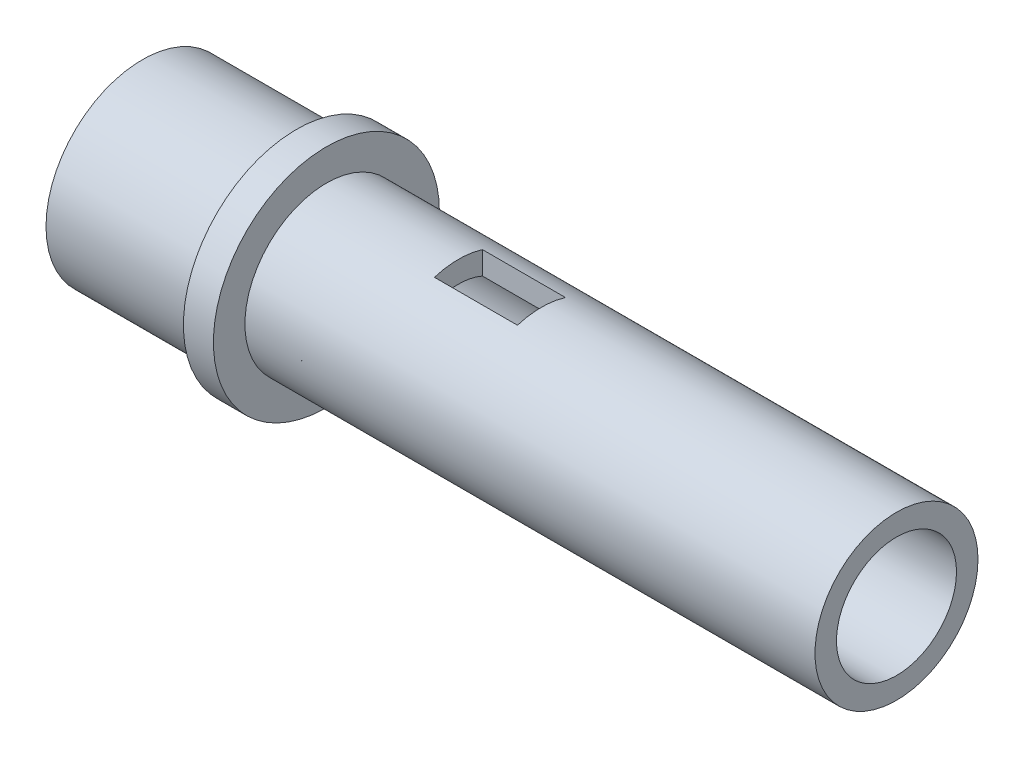
SolidWorks part; units mm, degrees
material "ABS"
ref_plane "Front Plane" through (0, 0, 0) normal (0, 0, 1) x (1, 0, 0)
ref_plane "Top Plane" through (0, 0, 0) normal (0, 1, 0) x (1, 0, 0)
ref_plane "Right Plane" through (0, 0, 0) normal (1, 0, 0) x (0, 0, -1)
sketch "Sketch1" plane through (0, 0, 0) normal (1, 0, 0) x (0, 0, -1)
  circle A0 centre (0, 0) radius 4.82
  dimension "D1" = 9.64
extrude "Boss-Extrude1" add sketch "Sketch1" along normal blind 7.7
sketch "Sketch2" plane through (7.7, 0, 0) normal (1, 0, 0) x (0, 0, -1)
  circle A0 centre (0, 0) radius 5.65
  dimension "D1" = 11.3
extrude "Boss-Extrude2" add sketch "Sketch2" along normal blind 1.5
sketch "Sketch3" plane through (9.2, 0, 0) normal (1, 0, 0) x (0, 0, -1)
  circle A0 centre (0, 0) radius 4.075
  dimension "D1" = 8.15
extrude "Boss-Extrude3" add sketch "Sketch3" along normal blind 28.5
sketch "Sketch4" plane through (37.7, 0, 0) normal (1, 0, 0) x (0, 0, -1)
  circle A0 centre (0, 0) radius 3
  dimension "D1" = 6
extrude "Cut-Extrude1" cut sketch "Sketch4" against normal through all
sketch "Sketch5" plane through (0, 0, 0) normal (-1, 0, 0) x (0, 0, 1)
  circle A0 centre (0, 0) radius 3.95
  dimension "D1" = 7.9
extrude "Cut-Extrude2" cut sketch "Sketch5" against normal blind 7.7
sketch "Sketch6" plane through (0, 0, 0) normal (0, 1, 0) x (1, 0, 0)
  line L0 (0, 4.82) -> (0, -4.82) construction
  line L1 (15.8, -1.2) -> (19.95, -1.2)
  line L2 (15.8, -1.2) -> (15.8, 1.2)
  line L3 (15.8, 1.2) -> (19.95, 1.2)
  line L4 (19.95, -1.2) -> (19.95, 1.2)
  line L5 (15.8, -1.2) -> (19.95, 1.2) construction
  line L6 (15.8, 1.2) -> (19.95, -1.2) construction
  point P0 (17.875, 0)
  dimension "D1" = 2.4
  dimension "D2" = 4.15
  dimension "D3" = 15.8
extrude "Cut-Extrude3" cut sketch "Sketch6" along normal blind 7.7
